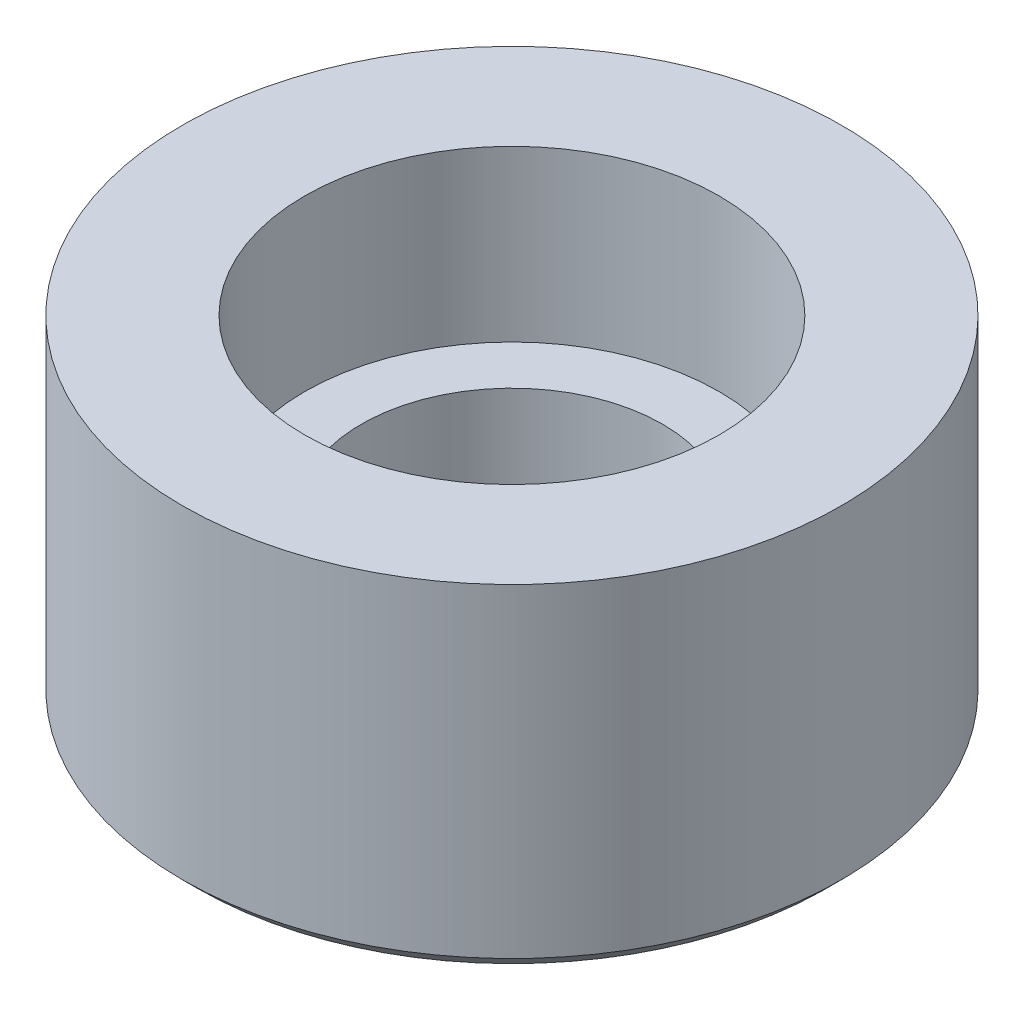
SolidWorks part; units mm, degrees
ref_plane "Front Plane" through (0, 0, 0) normal (0, 0, 1) x (1, 0, 0)
ref_plane "Top Plane" through (0, 0, 0) normal (0, 1, 0) x (1, 0, 0)
ref_plane "Right Plane" through (0, 0, 0) normal (1, 0, 0) x (0, 0, -1)
sketch "Sketch1" plane through (0, 0, 0) normal (0, 1, 0) x (1, 0, 0)
  circle A0 centre (0, 0) radius 8.75
  circle A1 centre (0, 0) radius 4
  dimension "D1" = 17.5
  dimension "D2" = 8
extrude "Boss-Extrude1" add sketch "Sketch1" along normal blind 9
ref_plane "Plane1" through (0, 9, 0) normal (0, 1, 0) x (1, 0, 0)
sketch "Sketch2" plane through (0, 9, 0) normal (0, 1, 0) x (1, 0, 0)
  circle A0 centre (0, 0) radius 5.5
  dimension "D1" = 11
extrude "Cut-Extrude1" cut sketch "Sketch2" against normal mid plane 9
chamfer "Chamfer1" distance 0.4 angle 45 1 edges at (0, 0, 8.75)
